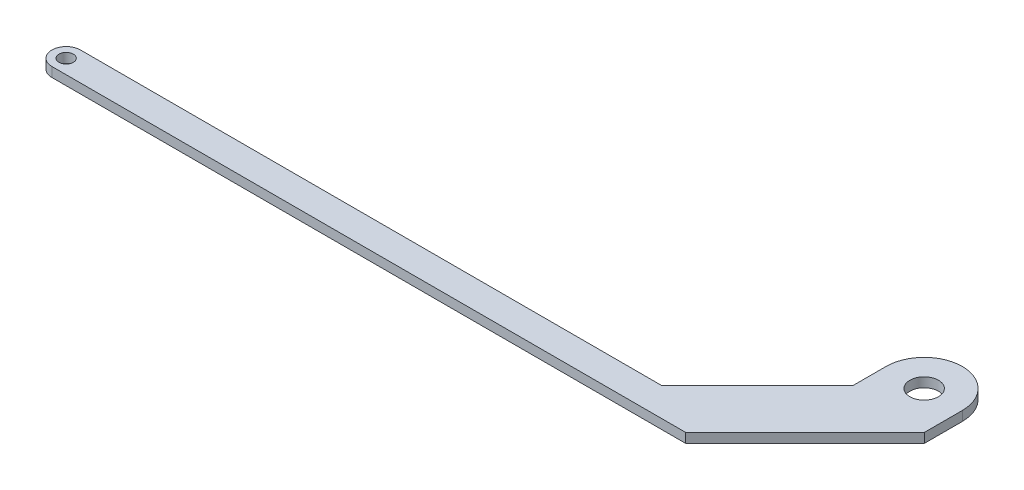
SolidWorks part; units mm, degrees
ref_plane "Front Plane" through (0, 0, 0) normal (0, 0, 1) x (1, 0, 0)
ref_plane "Top Plane" through (0, 0, 0) normal (0, 1, 0) x (1, 0, 0)
ref_plane "Right Plane" through (0, 0, 0) normal (1, 0, 0) x (0, 0, -1)
sketch "Sketch1" plane through (0, 0, 0) normal (0, 1, 0) x (1, 0, 0)
  line L0 (-4, 0) -> (-4, -3.5)
  line L1 (-4, -3.5) -> (-14, -13.5)
  line L2 (-14, -13.5) -> (-75, -13.5)
  line L3 (4, 0) -> (4, -3.9853)
  line L4 (4, -3.9853) -> (-8.5147, -16.5)
  line L5 (-8.5147, -16.5) -> (-75, -16.5)
  arc A0 (-4, 0) -> (4, 0) centre (0, 0) cw
  arc A1 (-75, -16.5) -> (-75, -13.5) centre (-75, -15) cw
  circle A2 centre (0, 0) radius 1.5
  circle A3 centre (-75, -15) radius 0.75
  dimension "D1" = 4
  dimension "D8" = 1.5
  dimension "D9" = 3
  dimension "D2" = 6
  dimension "D3" = 3
  dimension "D4" = 75
  dimension "D5" = 15
  dimension "D6" = 135
  dimension "D7" = 10
extrude "Boss-Extrude1" add sketch "Sketch1" along normal blind 1
